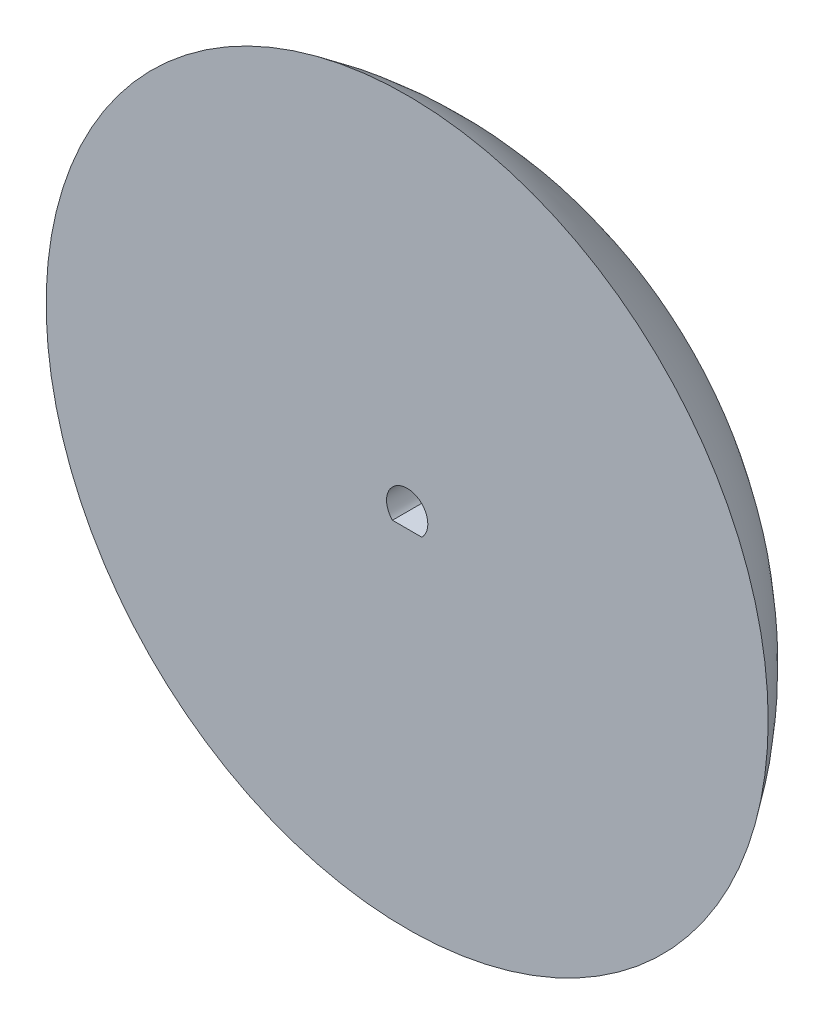
SolidWorks part; units mm, degrees
material "ABS"
ref_plane "Спереди" through (0, 0, 0) normal (0, 0, 1) x (1, 0, 0)
ref_plane "Сверху" through (0, 0, 0) normal (0, 1, 0) x (1, 0, 0)
ref_plane "Справа" through (0, 0, 0) normal (1, 0, 0) x (0, 0, -1)
other "Configuration Table"
sketch "Эскиз1" plane through (0, 0, 0) normal (1, 0, 0) x (0, 0, -1)
  line L0 (-81.7647, 0) -> (89.3122, 0) construction
  line L3 (15, 7) -> (15, 0)
  line L9 (0, 35) -> (0, 0)
  line L10 (0, 0) -> (15, 0)
  arc A0 (15, 7) -> (0, 35) centre (-18.6333, 7) ccw
  dimension "D1" = 15
  dimension "D2" = 35
  dimension "D3" = 7
revolve "Повернуть1" add sketch "Эскиз1" angle 360 about L0
sketch "Эскиз2" plane through (0, 0, 0) normal (0, 0, 1) x (1, 0, 0)
  line L0 (0, 2) -> (0, -2) construction
  line L1 (-1.4283, -1.4) -> (1.4283, -1.4)
  arc A1 (-1.4283, -1.4) -> (1.4283, -1.4) centre (0, 0) cw
  point P5 (0, -1.4)
  dimension "D1" = 2
  dimension "D2" = 3.4
  dimension "D3" = 2.8566
extrude "Вырез-Вытянуть1" cut sketch "Эскиз2" against normal blind 10.1
